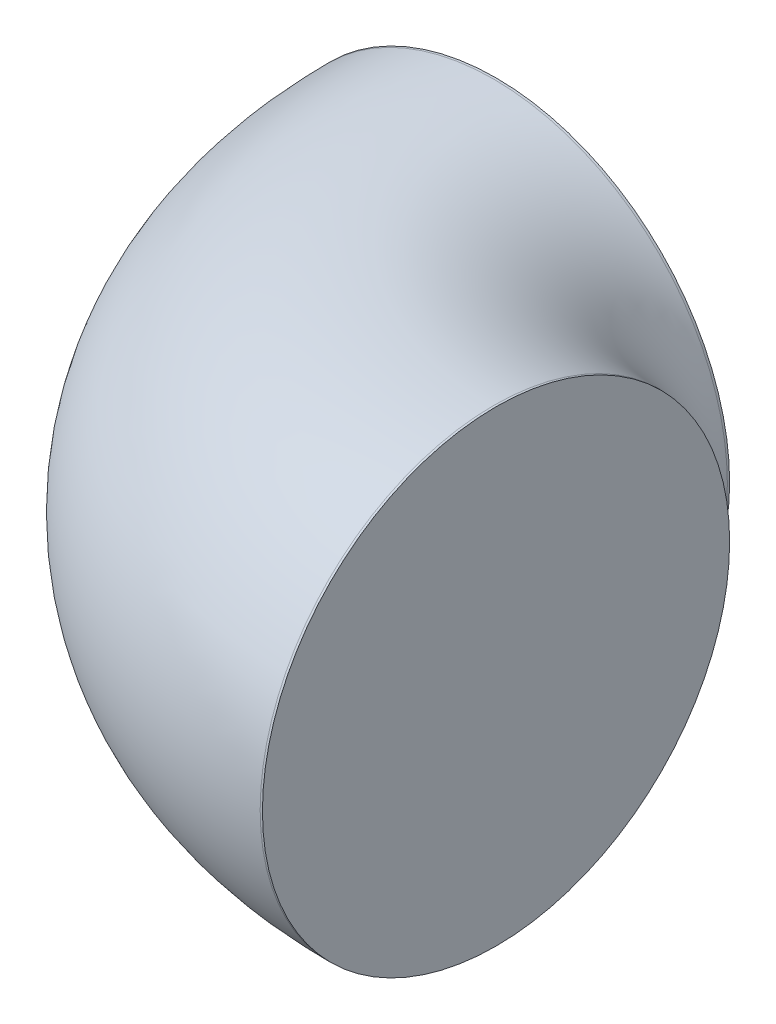
SolidWorks part; units mm, degrees
ref_plane "Front Plane" through (0, 0, 0) normal (0, 0, 1) x (1, 0, 0)
ref_plane "Top Plane" through (0, 0, 0) normal (0, 1, 0) x (1, 0, 0)
ref_plane "Right Plane" through (0, 0, 0) normal (1, 0, 0) x (0, 0, -1)
sketch "Sketch9" plane through (0, 0, 0) normal (0, 1, 0) x (1, 0, 0)
  line L0 (-58.0614, 23.2689) -> (-58.0614, 23.0149)
  line L1 (-26.3114, -8.7351) -> (-26.0574, -8.7351)
  arc A0 (-58.0614, 23.0149) -> (-26.3114, -8.7351) centre (-26.3114, 23.0149) ccw
  dimension "D3" = 31.75
  dimension "D1" = 0.254
  dimension "D2" = 0.254
sweep "Sweep2" add path "Sketch9" circular profile diameter 52.5 parameters "D3"=52.5
